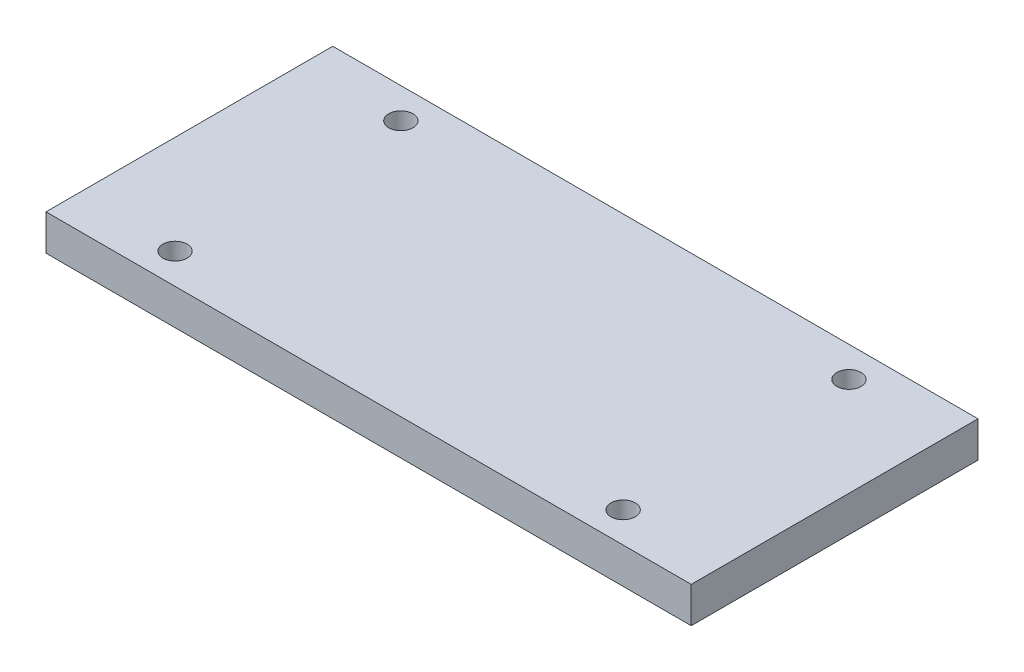
SolidWorks part; units mm, degrees
ref_plane "Front Plane" through (0, 0, 0) normal (0, 0, 1) x (1, 0, 0)
ref_plane "Top Plane" through (0, 0, 0) normal (0, 1, 0) x (1, 0, 0)
ref_plane "Right Plane" through (0, 0, 0) normal (1, 0, 0) x (0, 0, -1)
sketch "Sketch1" plane through (0, 0, 0) normal (0, 1, 0) x (1, 0, 0)
  line L1 (-57.15, -25.4) -> (57.15, -25.4)
  line L2 (-57.15, -25.4) -> (-57.15, 25.4)
  line L3 (-57.15, 25.4) -> (57.15, 25.4)
  line L4 (57.15, -25.4) -> (57.15, 25.4)
  line L5 (-57.15, -25.4) -> (57.15, 25.4) construction
  line L6 (-57.15, 25.4) -> (57.15, -25.4) construction
  point P0 (0, 0)
  dimension "D1" = 50.8
  dimension "D2" = 114.3
extrude "Boss-Extrude1" add sketch "Sketch1" along normal mid plane 6.35
sketch "Sketch2" plane through (0, -3.175, 0) normal (0, -1, 0) x (1, 0, 0)
  line L0 (0, 25.4) -> (0, -25.4) construction
  line L1 (57.15, 0) -> (-57.15, 0) construction
  line L4 (57.15, -25.4) -> (57.15, 25.4)
  line L5 (57.15, 25.4) -> (-57.15, 25.4)
  line L6 (-57.15, 25.4) -> (-57.15, -25.4)
  line L7 (-57.15, -25.4) -> (57.15, -25.4)
  line L8 (57.15, -25.4) -> (57.15, 25.4) construction
  line L9 (57.15, 25.4) -> (-57.15, 25.4) construction
  line L10 (-57.15, 25.4) -> (-57.15, -25.4) construction
  line L11 (-57.15, -25.4) -> (57.15, -25.4) construction
  point P2 (-39.6875, 20.0025)
  point P4 (-39.6875, -20.0025)
  point P8 (0, 0)
  point P11 (0, 0)
  point P12 (39.6875, -20.0025)
  point P14 (39.6875, 20.0025)
  point P15 (0, 0)
  dimension "D2" = 17.4625
  dimension "D3" = 5.3975
  dimension "D1" = 0
hole_wizard "#18 (0.1695) Diameter Hole1" positions "Sketch3" profile "Sketch4" hole size "#18" standard "ANSI Inch" end condition through all
sketch "Sketch3" plane through (0, -3.175, 0) normal (0, -1, 0) x (-1, 0, 0)
  point P0 (-39.6875, -20.0025)
  point P3 (-39.6875, 20.0025)
  point P6 (39.6875, 20.0025)
  point P9 (39.6875, -20.0025)
sketch "Sketch4" plane through (39.6875, -3.175, 20.0025) normal (1, 0, 0) x (0, 0, -1)
  line L0 (0, 0) -> (0, 6.35)
  line L1 (0, 6.35) -> (2.1526, 6.35)
  line L2 (2.1526, 6.35) -> (2.1526, 0)
  line L5 (2.1526, 0) -> (0, 0)
  line L11 (0, -6.35) -> (0, 107.95) construction
  dimension "Thru Hole Dia." = 4.3053
  dimension "Thru Hole Depth" = 6.35
